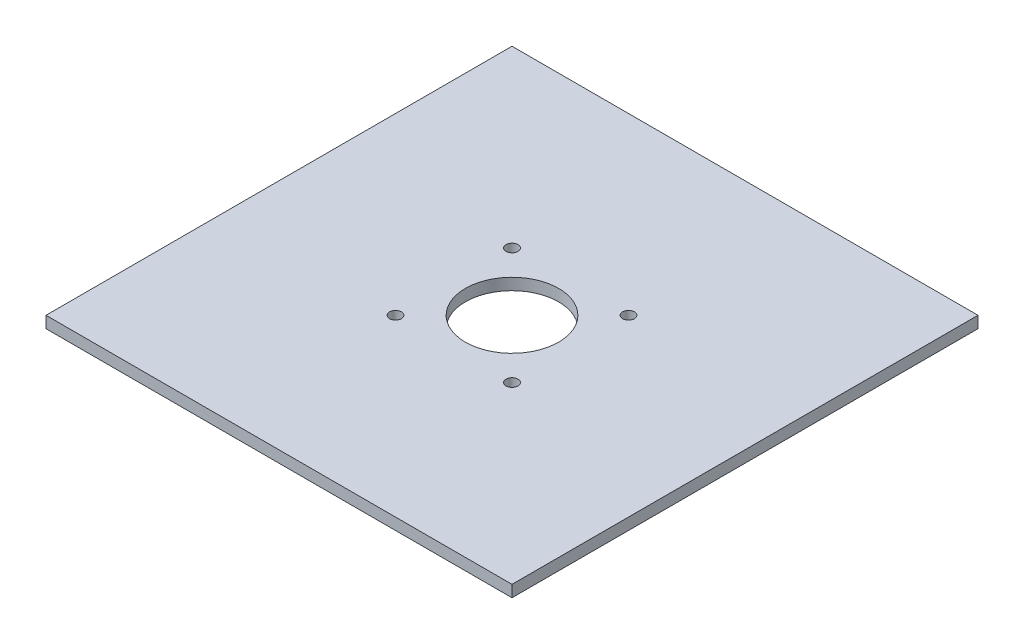
SolidWorks part; units mm, degrees
ref_plane "Front Plane" through (0, 0, 0) normal (0, 0, 1) x (1, 0, 0)
ref_plane "Top Plane" through (0, 0, 0) normal (0, 1, 0) x (1, 0, 0)
ref_plane "Right Plane" through (0, 0, 0) normal (1, 0, 0) x (0, 0, -1)
sketch "Sketch1" plane through (0, 0, 0) normal (0, 1, 0) x (1, 0, 0)
  line L1 (100, 100) -> (-100, 100)
  line L2 (100, 100) -> (100, -100)
  line L3 (100, -100) -> (-100, -100)
  line L4 (-100, 100) -> (-100, -100)
  line L5 (100, 100) -> (-100, -100) construction
  line L6 (100, -100) -> (-100, 100) construction
  circle A0 centre (-25, -25) radius 2.55
  circle A1 centre (25, -25) radius 2.55
  circle A2 centre (25, 25) radius 2.55
  circle A3 centre (-25, 25) radius 2.55
  circle A4 centre (0, 0) radius 20
  point P0 (0, 0)
  dimension "D3" = 5.1
  dimension "D4" = 5.1
  dimension "D5" = 5.1
  dimension "D6" = 5.1
  dimension "D11" = 40
  dimension "D2" = 200
  dimension "D7" = 50
  dimension "D8" = 50
  dimension "D9" = 50
  dimension "D10" = 50
extrude "Boss-Extrude1" add sketch "Sketch1" along normal blind 5
